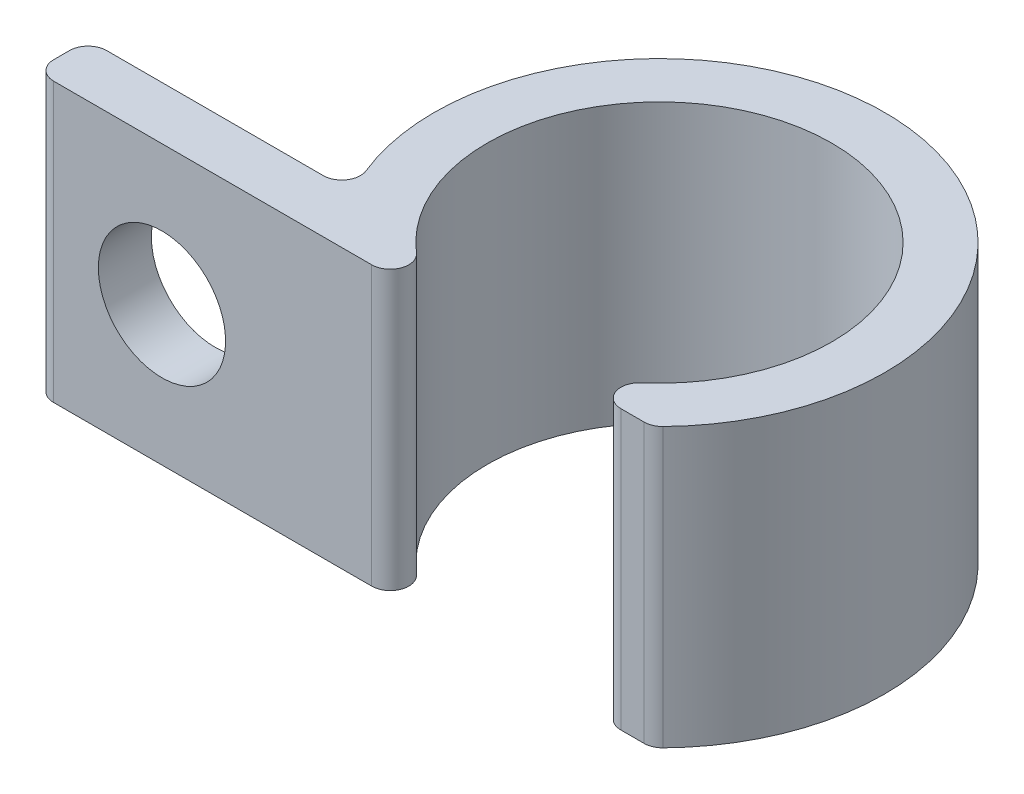
SolidWorks part; units mm, degrees
ref_plane "Plan de face" through (0, 0, 0) normal (0, 0, 1) x (1, 0, 0)
ref_plane "Plan de dessus" through (0, 0, 0) normal (0, 1, 0) x (1, 0, 0)
ref_plane "Plan de droite" through (0, 0, 0) normal (1, 0, 0) x (0, 0, -1)
sketch "Esquisse1" plane through (0, 0, 0) normal (0, 1, 0) x (1, 0, 0)
  line L0 (0, 0) -> (12, 0)
  line L1 (21.4, 0) -> (22.2758, 0)
  line L2 (8.1731, 2) -> (0, 2)
  line L3 (-0.7, 1.3) -> (-0.7, 0.7)
  arc A0 (12, 0) -> (12.4569, 1.2303) centre (12, 0.7) ccw
  arc A1 (12.4569, 1.2303) -> (20.9431, 1.2303) centre (16.7, 6.1544) cw
  arc A2 (20.9431, 1.2303) -> (21.4, 0) centre (21.4, 0.7) ccw
  arc A3 (22.2758, 0) -> (22.7762, 0.2105) centre (22.2758, 0.7) ccw
  arc A4 (22.7762, 0.2105) -> (8.8219, 2.9628) centre (16.7, 6.1544) ccw
  arc A5 (8.8219, 2.9628) -> (8.1731, 2) centre (8.1731, 2.7) cw
  arc A6 (0, 2) -> (-0.7, 1.3) centre (0, 1.3) ccw
  arc A7 (-0.7, 0.7) -> (0, 0) centre (0, 0.7) ccw
  point P0 (19.7584, 1.1202)
  point P5 (6.4344, 14.8167)
  point P22 (0, 0)
  point P23 (19.72, 13.7426)
  point P24 (12, 0)
  point P25 (0, 0)
  dimension "D2" = 0.7
  dimension "D3" = 6.5
  dimension "D4" = 8.5
  dimension "D1" = 12
  dimension "D5" = 2
  dimension "D6" = 9.4
extrude "Boss.-Extru.1" add sketch "Esquisse1" along normal blind 10.5
hole_wizard "Dégagement M41" positions "Esquisse2" profile "Esquisse3" hole size "M4" standard "DIN" end condition through all
sketch "Esquisse2" plane through (0, 0, -2) normal (0, 0, -1) x (-1, 0, 0)
  line L0 (-8.1731, 5.25) -> (0, 5.25) construction
  line L1 (-8.1731, 10.5) -> (-8.1731, 0) construction
  line L2 (0, 10.5) -> (0, 0) construction
  point P0 (-4.0866, 5.25)
  point P10 (0, 0)
sketch "Esquisse3" plane through (4.0866, 5.25, -2) normal (1, 0, 0) x (0, 1, 0)
  line L0 (0, 0) -> (0, 2)
  line L1 (0, 2) -> (2.4, 2)
  line L2 (2.4, 2) -> (2.4, 0)
  line L5 (2.4, 0) -> (0, 0)
  line L11 (0, -6.35) -> (0, 107.95) construction
  dimension "Diamètre du perçage jusqu'au prochain" = 4.8
  dimension "Profondeur du perçage jusqu'au prochain" = 2
equation "\"e\"= 2mm"
equation "\"r\"= 0.7mm"
equation "\"D2@Esquisse1\"=\"r\""
equation "\"rcable1\" = 3.5"
equation "\"D1@Boss.-Extru.1\"=\"rcable1\"*3"
equation "\"rcable2\"= 2"
equation "\"D3@Esquisse1\"=\"rcable1\"+\"rcable2\"+1"
equation "\"D4@Esquisse1\"=\"rcable1\"+\"rcable2\"+\"e\"+1"
equation "\"D6@Esquisse1\"=\"rcable1\"*2+\"r\"*2+1"
